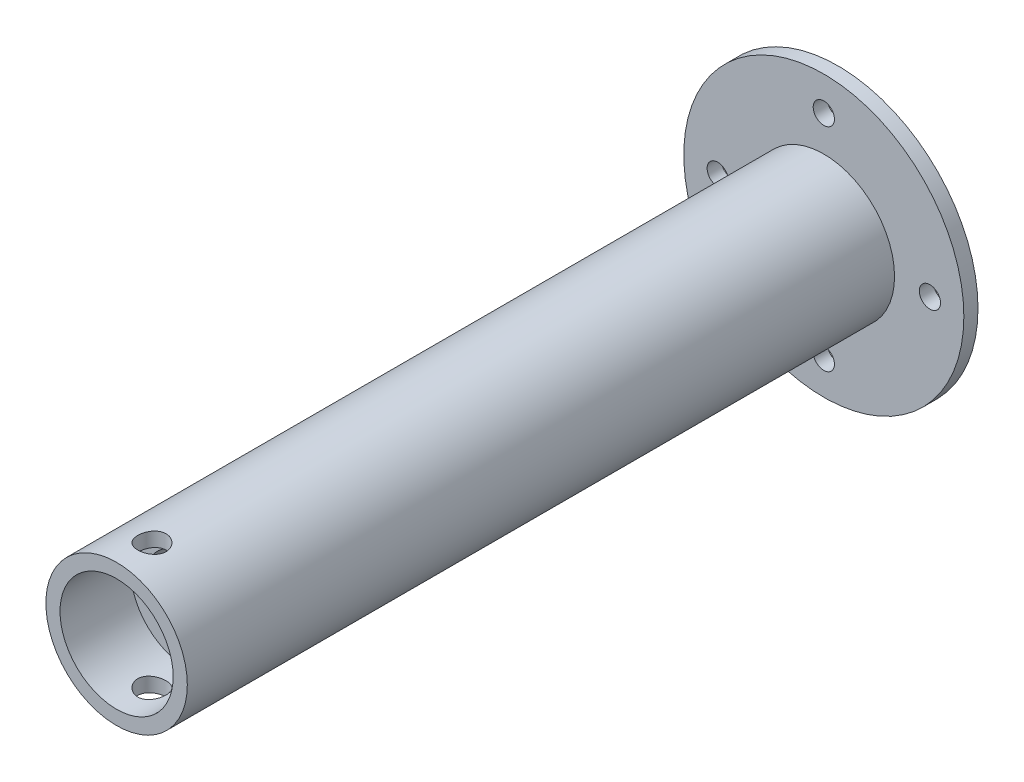
SolidWorks part; units mm, degrees
ref_plane "Front Plane" through (0, 0, 0) normal (0, 0, 1) x (1, 0, 0)
ref_plane "Top Plane" through (0, 0, 0) normal (0, 1, 0) x (1, 0, 0)
ref_plane "Right Plane" through (0, 0, 0) normal (1, 0, 0) x (0, 0, -1)
sketch "Sketch1" plane through (0, 0, 0) normal (0, 0, 1) x (1, 0, 0)
  circle A0 centre (0, 0) radius 19.8
extrude "Boss-Extrude1" add sketch "Sketch1" along normal blind 2
sketch "Sketch2" plane through (0, 0, 2) normal (0, 0, 1) x (1, 0, 0)
  circle A1 centre (0, 0) radius 15
  circle A2 centre (0, 15) radius 1.5
  circle A3 centre (15, 0) radius 1.5
  circle A4 centre (0, -15) radius 1.5
  circle A5 centre (-15, 0) radius 1.5
  point P15 (0, 0)
  dimension "D1" = 4
extrude "Cut-Extrude1" cut sketch "Sketch2" against normal blind 5 contours A1 A2 | A1 A2 | A3 | A4 | A5
sketch "Sketch3" plane through (0, 0, 2) normal (0, 0, 1) x (1, 0, 0)
  circle A0 centre (0, 0) radius 10
extrude "Boss-Extrude2" add sketch "Sketch3" along normal blind 100
sketch "Sketch4" plane through (0, 0, 102) normal (0, 0, 1) x (1, 0, 0)
  circle A0 centre (0, 0) radius 6
extrude "Cut-Extrude3" cut sketch "Sketch4" against normal blind 200
sketch "Sketch6" plane through (0, 0, 102) normal (0, 0, 1) x (1, 0, 0)
  circle A0 centre (0, 0) radius 8
extrude "Cut-Extrude4" cut sketch "Sketch6" against normal blind 10
ref_plane "Plane1" through (0, 10, 0) normal (0, 1, 0) x (1, 0, 0)
sketch "Sketch13" plane through (0, 10, 0) normal (0, 1, 0) x (1, 0, 0)
  line L0 (0, -102) -> (0, -97)
  line L1 (-10, -102) -> (10, -102) construction
  circle A0 centre (0, -97) radius 2
extrude "Cut-Extrude7" cut sketch "Sketch13" against normal blind 20
